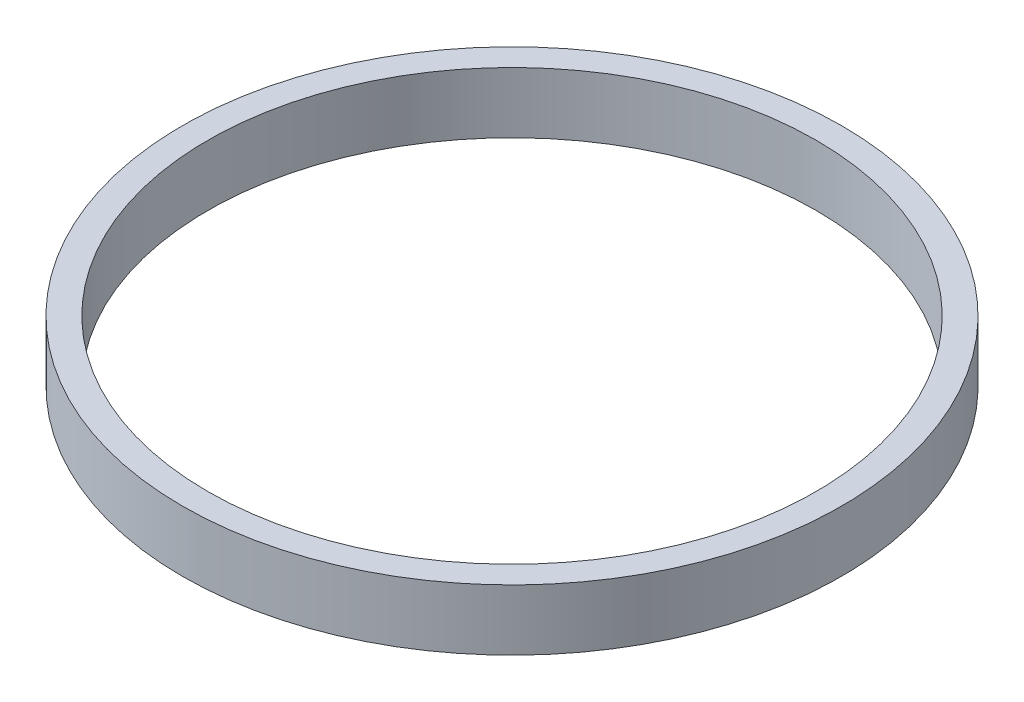
SolidWorks part; units mm, degrees
ref_plane "Front Plane" through (0, 0, 0) normal (0, 0, 1) x (1, 0, 0)
ref_plane "Top Plane" through (0, 0, 0) normal (0, 1, 0) x (1, 0, 0)
ref_plane "Right Plane" through (0, 0, 0) normal (1, 0, 0) x (0, 0, -1)
sketch "Sketch1" plane through (0, 0, 0) normal (0, 1, 0) x (1, 0, 0)
  circle A0 centre (0, 0) radius 32.5
  circle A1 centre (0, 0) radius 30
  dimension "D1" = 65
  dimension "D2" = 60
extrude "Boss-Extrude1" add sketch "Sketch1" along normal blind 6
